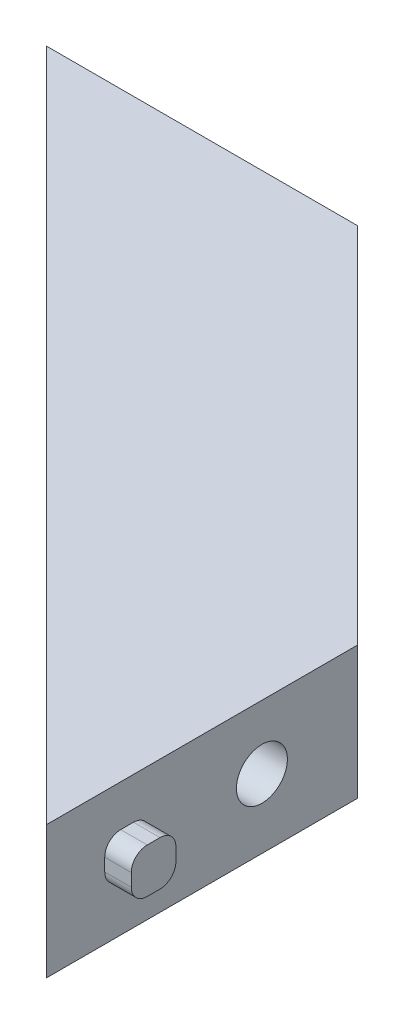
SolidWorks part; units mm, degrees
ref_plane "Front Plane" through (0, 0, 0) normal (0, 0, 1) x (1, 0, 0)
ref_plane "Top Plane" through (0, 0, 0) normal (0, 1, 0) x (1, 0, 0)
ref_plane "Right Plane" through (0, 0, 0) normal (1, 0, 0) x (0, 0, -1)
sketch "Sketch1" plane through (0, 0, 0) normal (0, 1, 0) x (1, 0, 0)
  line L0 (-31.75, 31.75) -> (31.75, -31.75)
  line L3 (-31.75, 31.75) -> (31.75, 31.75)
  line L4 (31.75, -31.75) -> (31.75, 31.75)
  dimension "D1" = 63.5
  dimension "D2" = 63.5
extrude "Boss-Extrude1" add sketch "Sketch1" along normal blind 12.5
sketch "Sketch2" plane through (31.75, 0, 0) normal (1, 0, 0) x (0, 0, -1)
  line L0 (-31.75, 0) -> (31.75, 0) construction
  line L1 (26.05, 4.4) -> (27.25, 4.4)
  line L2 (24.55, 5.9) -> (24.55, 7.1)
  line L3 (26.05, 8.6) -> (27.25, 8.6)
  line L4 (28.75, 5.9) -> (28.75, 7.1)
  line L5 (24.55, 4.4) -> (28.75, 8.6) construction
  line L6 (24.55, 8.6) -> (28.75, 4.4) construction
  line L7 (31.75, 12.5) -> (31.75, 0) construction
  line L8 (11.85, 5.9) -> (11.85, 7.1)
  line L9 (13.35, 4.4) -> (14.55, 4.4)
  line L10 (16.05, 5.9) -> (16.05, 7.1)
  line L11 (13.35, 8.6) -> (14.55, 8.6)
  line L12 (-0.85, 5.9) -> (-0.85, 7.1)
  line L13 (0.65, 4.4) -> (1.85, 4.4)
  line L14 (3.35, 5.9) -> (3.35, 7.1)
  line L15 (0.65, 8.6) -> (1.85, 8.6)
  line L16 (-13.55, 5.9) -> (-13.55, 7.1)
  line L17 (-12.05, 4.4) -> (-10.85, 4.4)
  line L18 (-9.35, 5.9) -> (-9.35, 7.1)
  line L19 (-12.05, 8.6) -> (-10.85, 8.6)
  line L20 (-26.25, 5.9) -> (-26.25, 7.1)
  line L21 (-24.75, 4.4) -> (-23.55, 4.4)
  line L22 (-22.05, 5.9) -> (-22.05, 7.1)
  line L23 (-24.75, 8.6) -> (-23.55, 8.6)
  arc A0 (27.25, 4.4) -> (28.75, 5.9) centre (27.25, 5.9) ccw
  arc A1 (26.05, 4.4) -> (24.55, 5.9) centre (26.05, 5.9) cw
  arc A2 (24.55, 7.1) -> (26.05, 8.6) centre (26.05, 7.1) cw
  arc A3 (27.25, 8.6) -> (28.75, 7.1) centre (27.25, 7.1) cw
  arc A4 (11.85, 7.1) -> (13.35, 8.6) centre (13.35, 7.1) cw
  arc A5 (13.35, 4.4) -> (11.85, 5.9) centre (13.35, 5.9) cw
  arc A6 (14.55, 4.4) -> (16.05, 5.9) centre (14.55, 5.9) ccw
  arc A7 (14.55, 8.6) -> (16.05, 7.1) centre (14.55, 7.1) cw
  arc A8 (-0.85, 7.1) -> (0.65, 8.6) centre (0.65, 7.1) cw
  arc A9 (0.65, 4.4) -> (-0.85, 5.9) centre (0.65, 5.9) cw
  arc A10 (1.85, 4.4) -> (3.35, 5.9) centre (1.85, 5.9) ccw
  arc A11 (1.85, 8.6) -> (3.35, 7.1) centre (1.85, 7.1) cw
  arc A12 (-13.55, 7.1) -> (-12.05, 8.6) centre (-12.05, 7.1) cw
  arc A13 (-12.05, 4.4) -> (-13.55, 5.9) centre (-12.05, 5.9) cw
  arc A14 (-10.85, 4.4) -> (-9.35, 5.9) centre (-10.85, 5.9) ccw
  arc A15 (-10.85, 8.6) -> (-9.35, 7.1) centre (-10.85, 7.1) cw
  arc A16 (-26.25, 7.1) -> (-24.75, 8.6) centre (-24.75, 7.1) cw
  arc A17 (-24.75, 4.4) -> (-26.25, 5.9) centre (-24.75, 5.9) cw
  arc A18 (-23.55, 4.4) -> (-22.05, 5.9) centre (-23.55, 5.9) ccw
  arc A19 (-23.55, 8.6) -> (-22.05, 7.1) centre (-23.55, 7.1) cw
  point P0 (26.65, 6.5)
  dimension "D5" = 1.5
  dimension "D1" = 4.2
  dimension "D2" = 4.2
  dimension "D3" = 4.4
  dimension "D4" = 3
  dimension "D6" = 5
extrude "Boss-Extrude2" add sketch "Sketch2" along normal blind 2.5
sketch "Sketch3" plane through (0, 0, -31.75) normal (0, 0, -1) x (-1, 0, 0)
  line L0 (-31.75, 12.5) -> (-31.75, 0) construction
  line L1 (-26.05, 4.4) -> (-27.25, 4.4)
  line L2 (-24.55, 5.9) -> (-24.55, 7.1)
  line L3 (-26.05, 8.6) -> (-27.25, 8.6)
  line L4 (-28.75, 5.9) -> (-28.75, 7.1)
  line L5 (-24.55, 4.4) -> (-28.75, 8.6) construction
  line L6 (-24.55, 8.6) -> (-28.75, 4.4) construction
  line L7 (-31.75, 0) -> (31.75, 0) construction
  line L8 (-11.85, 5.9) -> (-11.85, 7.1)
  line L9 (-13.35, 4.4) -> (-14.55, 4.4)
  line L10 (-16.05, 5.9) -> (-16.05, 7.1)
  line L11 (-13.35, 8.6) -> (-14.55, 8.6)
  line L12 (0.85, 5.9) -> (0.85, 7.1)
  line L13 (-0.65, 4.4) -> (-1.85, 4.4)
  line L14 (-3.35, 5.9) -> (-3.35, 7.1)
  line L15 (-0.65, 8.6) -> (-1.85, 8.6)
  line L16 (13.55, 5.9) -> (13.55, 7.1)
  line L17 (12.05, 4.4) -> (10.85, 4.4)
  line L18 (9.35, 5.9) -> (9.35, 7.1)
  line L19 (12.05, 8.6) -> (10.85, 8.6)
  line L20 (26.25, 5.9) -> (26.25, 7.1)
  line L21 (24.75, 4.4) -> (23.55, 4.4)
  line L22 (22.05, 5.9) -> (22.05, 7.1)
  line L23 (24.75, 8.6) -> (23.55, 8.6)
  arc A0 (-26.05, 4.4) -> (-24.55, 5.9) centre (-26.05, 5.9) ccw
  arc A1 (-27.25, 4.4) -> (-28.75, 5.9) centre (-27.25, 5.9) cw
  arc A2 (-27.25, 8.6) -> (-28.75, 7.1) centre (-27.25, 7.1) ccw
  arc A3 (-24.55, 7.1) -> (-26.05, 8.6) centre (-26.05, 7.1) ccw
  arc A4 (-11.85, 7.1) -> (-13.35, 8.6) centre (-13.35, 7.1) ccw
  arc A5 (-13.35, 4.4) -> (-11.85, 5.9) centre (-13.35, 5.9) ccw
  arc A6 (-14.55, 4.4) -> (-16.05, 5.9) centre (-14.55, 5.9) cw
  arc A7 (-14.55, 8.6) -> (-16.05, 7.1) centre (-14.55, 7.1) ccw
  arc A8 (0.85, 7.1) -> (-0.65, 8.6) centre (-0.65, 7.1) ccw
  arc A9 (-0.65, 4.4) -> (0.85, 5.9) centre (-0.65, 5.9) ccw
  arc A10 (-1.85, 4.4) -> (-3.35, 5.9) centre (-1.85, 5.9) cw
  arc A11 (-1.85, 8.6) -> (-3.35, 7.1) centre (-1.85, 7.1) ccw
  arc A12 (13.55, 7.1) -> (12.05, 8.6) centre (12.05, 7.1) ccw
  arc A13 (12.05, 4.4) -> (13.55, 5.9) centre (12.05, 5.9) ccw
  arc A14 (10.85, 4.4) -> (9.35, 5.9) centre (10.85, 5.9) cw
  arc A15 (10.85, 8.6) -> (9.35, 7.1) centre (10.85, 7.1) ccw
  arc A16 (26.25, 7.1) -> (24.75, 8.6) centre (24.75, 7.1) ccw
  arc A17 (24.75, 4.4) -> (26.25, 5.9) centre (24.75, 5.9) ccw
  arc A18 (23.55, 4.4) -> (22.05, 5.9) centre (23.55, 5.9) cw
  arc A19 (23.55, 8.6) -> (22.05, 7.1) centre (23.55, 7.1) ccw
  point P0 (-26.65, 6.5)
  dimension "D5" = 1.5
  dimension "D1" = 4.2
  dimension "D2" = 4.2
  dimension "D3" = 3
  dimension "D4" = 4.4
  dimension "D6" = 5
extrude "Boss-Extrude3" add sketch "Sketch3" along normal blind 2.5
sketch "Sketch4" plane through (0, 12.5, 0) normal (0, 1, 0) x (1, 0, 0)
  line L0 (31.75, -2.4343) -> (-2.4343, 31.75)
  line L1 (31.75, -31.75) -> (31.75, 31.75) construction
  line L2 (31.75, 31.75) -> (-31.75, 31.75) construction
  line L3 (31.75, -2.4343) -> (35.7154, -2.4343)
  line L4 (35.7154, -2.4343) -> (35.7154, 36.2688)
  line L5 (35.7154, 36.2688) -> (-2.4343, 36.2688)
  line L6 (-2.4343, 36.2688) -> (-2.4343, 31.75)
extrude "Cut-Extrude1" cut sketch "Sketch4" against normal through all
sketch "Sketch5" plane through (34.25, 0, 0) normal (1, 0, 0) x (0, 0, -1)
  circle A0 centre (-11.45, 6.5) radius 2.4
extrude "Cut-Extrude2" cut sketch "Sketch5" against normal blind 32.5
sketch "Sketch6" plane through (0, 0, -34.25) normal (0, 0, -1) x (-1, 0, 0)
  circle A0 centre (11.45, 6.5) radius 2.4
extrude "Cut-Extrude3" cut sketch "Sketch6" against normal blind 32.5
sketch3d "3DSketch2"
  line L0 (31.75, 6.5, 11.45) -> (-14.4564, 6.5, 11.45)
  line L1 (9.05, 6.5, 11.45) -> (31.75, 6.5, 11.45) construction
  line L2 (-11.45, 6.5, -31.75) -> (-11.45, 6.5, 17.2063)
  line L3 (-11.45, 6.5, -9.05) -> (-11.45, 6.5, -31.75) construction
  line L4 (10.0938, 6.5, 11.45) -> (10.0938, 6.5, 16.2762)
  line L5 (-11.45, 6.5, -9.8112) -> (-15.2666, 6.5, -9.8112)
  line L6 (10.0938, 6.5, 16.2762) -> (10.0938, 11.0198, 16.2762)
  line L7 (-15.2666, 6.5, -9.8112) -> (-15.2666, 2.4884, -9.8112)
ref_plane "Plane1" through (10.0938, 0, 0) normal (-1, 0, 0) x (0, 0, 1)
ref_plane "Plane2" through (0, 0, -9.8112) normal (0, 0, 1) x (1, 0, 0)
sketch "Sketch7" plane through (0, 0, -9.8112) normal (0, 0, 1) x (1, 0, 0)
  circle A0 centre (-11.45, 6.5) radius 4.25
extrude "Cut-Extrude4" cut sketch "Sketch7" against normal blind 12.5 and the other way blind 12.5
sketch "Sketch8" plane through (10.0938, 0, 0) normal (-1, 0, 0) x (0, 0, 1)
  circle A0 centre (11.45, 6.5) radius 4.25
extrude "Cut-Extrude5" cut sketch "Sketch8" against normal blind 12.5 and the other way blind 12.5
